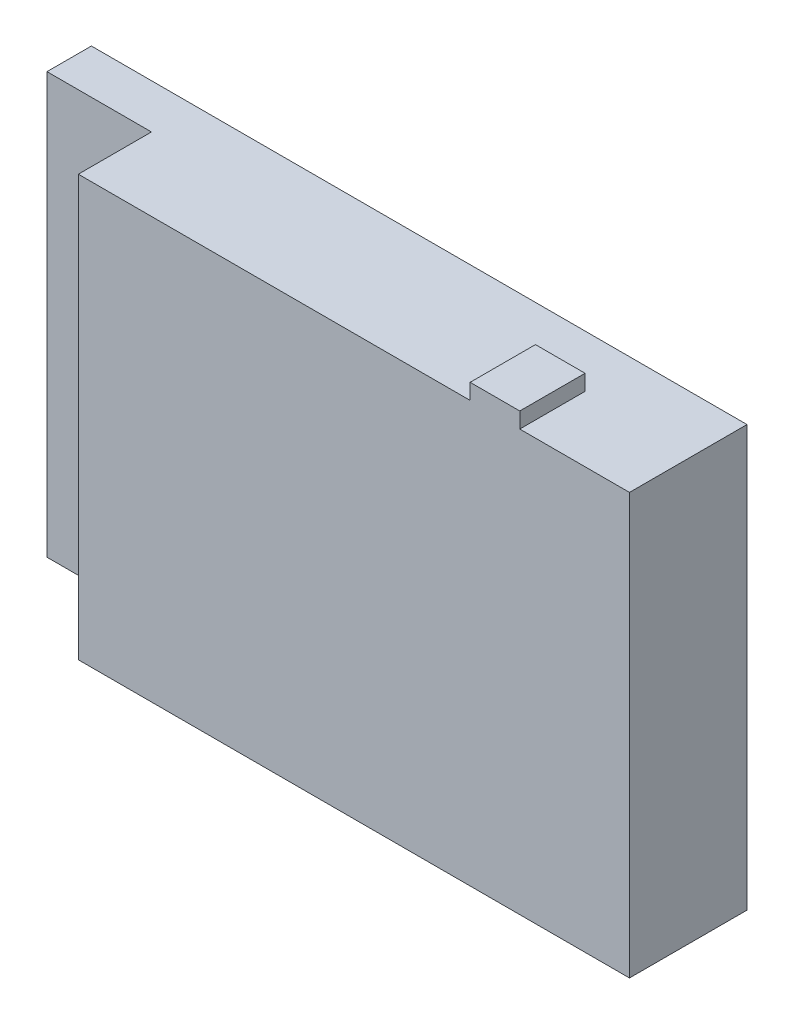
SolidWorks part; units mm, degrees
ref_plane "前视基准面" through (0, 0, 0) normal (0, 0, 1) x (1, 0, 0)
ref_plane "上视基准面" through (0, 0, 0) normal (0, 1, 0) x (1, 0, 0)
ref_plane "右视基准面" through (0, 0, 0) normal (1, 0, 0) x (0, 0, -1)
other "Configuration Table"
sketch "草图1" plane through (0, 0, 0) normal (0, 0, 1) x (1, 0, 0)
  line L6 (-12.55, -8.05) -> (12.55, -8.05)
  line L11 (-12.55, -8.05) -> (-12.55, 8.05)
  line L12 (-12.55, 8.05) -> (12.55, 8.05)
  line L13 (12.55, -8.05) -> (12.55, 8.05)
  line L14 (-12.55, -8.05) -> (12.55, 8.05) construction
  line L15 (-12.55, 8.05) -> (12.55, -8.05) construction
  line L16 (6.45, 8.05) -> (8.35, 8.05)
  line L17 (6.45, 8.05) -> (6.45, 8.65)
  line L18 (6.45, 8.65) -> (8.35, 8.65)
  line L19 (8.35, 8.05) -> (8.35, 8.65)
  point P0 (0, 0)
  dimension "D1" = 16.1
  dimension "D2" = 25.1
  dimension "D4" = 20.9
  dimension "D5" = 16.7
  dimension "D3" = 6.1
extrude "凸台-拉伸1" add sketch "草图1" along normal blind 4.5
sketch "草图2" plane through (0, 0, 0) normal (0, 0, -1) x (-1, 0, 0)
  line L0 (-8.35, 8.05) -> (-8.35, 8.65) construction
  line L1 (-6.45, 8.05) -> (-8.35, 8.05)
  line L2 (-6.45, 8.05) -> (-6.45, 8.65)
  line L3 (-6.45, 8.65) -> (-8.35, 8.65)
  line L4 (-8.35, 8.05) -> (-8.35, 8.65)
  line L5 (-6.45, 8.65) -> (-8.35, 8.65) construction
  point P8 (0, 0)
  point P9 (-5.7552, 8.3658)
extrude "切除-拉伸1" cut sketch "草图2" against normal blind 2
sketch "草图3" plane through (0, 0, 4.5) normal (0, 0, 1) x (1, 0, 0)
  line L0 (-12.55, -8.05) -> (-12.55, 8.05) construction
  line L1 (-12.55, 8.05) -> (-8.55, 8.05)
  line L2 (-12.55, 8.05) -> (-12.55, -8.05)
  line L3 (-12.55, -8.05) -> (-8.55, -8.05)
  line L4 (-8.55, 8.05) -> (-8.55, -8.05)
  line L5 (-12.55, 8.05) -> (6.45, 8.05) construction
  line L6 (-12.55, -8.05) -> (12.55, -8.05) construction
  dimension "D1" = 4
extrude "切除-拉伸2" cut sketch "草图3" against normal offset from surface (2.8 mm away) 1.7 up to face at (0, 0, 0)
